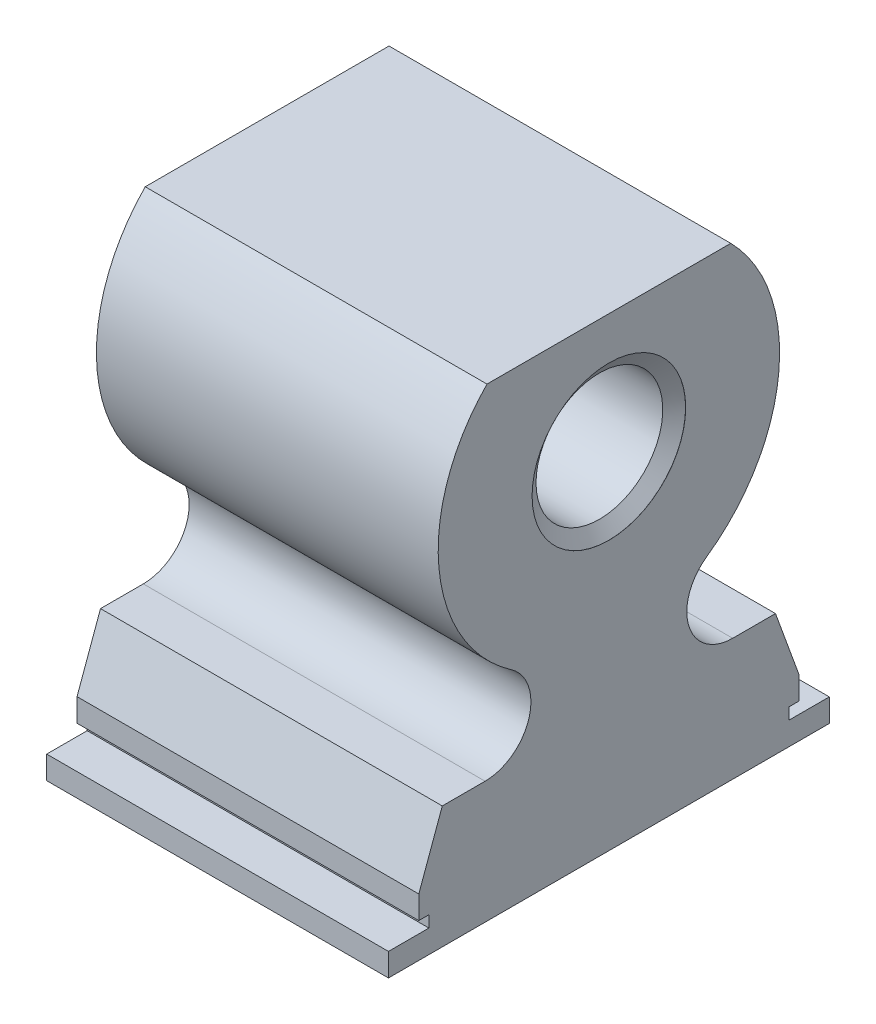
SolidWorks part; units mm, degrees
extrude "Body" add sketch "BodySke" along normal blind 8.9
sketch "BodySke" plane through (0, 0, 0) normal (1, 0, 0) x (0, 0, -1)
  line L0 (-5.74, -9) -> (5.74, -9)
  line L1 (5.74, -9) -> (5.74, -8.4)
  line L2 (5.74, -8.4) -> (4.6867, -8.4)
  line L3 (-5.74, -9) -> (-5.74, -8.4)
  line L4 (-5.74, -8.4) -> (-4.6867, -8.4)
  line L5 (4.6867, -8.4) -> (4.6867, -8.1)
  line L6 (-4.6867, -8.4) -> (-4.6867, -8.1)
  line L7 (4.6867, -8.1) -> (4.95, -8.1)
  line L8 (-4.6867, -8.1) -> (-4.95, -8.1)
  line L9 (-3.2237, -5.82) -> (-4.3385, -5.82)
  line L10 (0, -0.7) -> (4.5045, -0.7) construction
  line L11 (4.3385, -5.82) -> (3.2237, -5.82)
  line L12 (0, 7.62) -> (0, -11.43) construction
  line L13 (7.62, 0) -> (-7.62, 0) construction
  line L14 (2.03, -2.8908) -> (2.03, -7.62) construction
  line L15 (-2.03, -2.8908) -> (-2.03, -7.62) construction
  line L16 (4.3385, -5.82) -> (4.95, -7.5)
  line L17 (4.95, -7.5) -> (4.95, -8.1)
  line L18 (-4.3385, -5.82) -> (-4.95, -7.5)
  line L19 (-4.95, -7.5) -> (-4.95, -8.1)
  circle A0 centre (0, 0) radius 1.65
  arc A1 (2.5412, -3.6469) -> (-2.5412, -3.6469) centre (0, 0) ccw
  arc A2 (3.2237, -5.82) -> (2.5412, -3.6469) centre (3.2237, -4.6263) cw
  arc A3 (-2.5412, -3.6469) -> (-3.2237, -5.82) centre (-3.2237, -4.6263) cw
  dimension "Thread_min" = 3.3
  dimension "C_dia" = 8.89
  dimension "J_dim" = 4.06
  dimension "E_dim" = 11.48
  dimension "D_dim" = 3.18
  dimension "Clinch_ht" = 0.6
  dimension "Side_ht" = 0.6
  dimension "Groove_wid" = 0.3
  dimension "A_dim" = 9.9
  dimension "Groove_overall" = 9.3733
  dimension "F_dim" = 9
  dimension "D12" = 20
  dimension "Advance" = 0.7
cosmetic thread "ThreadCosmetic" [suppressed]
revolve "EndChamfer" cut sketch "EndChamferSke" angle 360 about L11
sketch "EndChamferSke" plane through (0, 0, 0) normal (0, 0, 1) x (1, 0, 0)
  line L0 (-0.254, 2) -> (0.0025, 2)
  line L2 (0.0025, 2) -> (0.2475, 1.65)
  line L3 (0.2475, 1.65) -> (-0.254, 1.65)
  line L4 (-0.254, 1.65) -> (-0.254, 2)
  line L5 (9.154, 2) -> (8.8975, 2)
  line L6 (8.8975, 2) -> (8.6525, 1.65)
  line L7 (8.6525, 1.65) -> (9.154, 1.65)
  line L8 (9.154, 1.65) -> (9.154, 2)
  line L9 (0, 4.445) -> (0, -3.6469) construction
  line L10 (8.9, -3.6469) -> (8.9, 4.445) construction
  line L11 (-5.1059, 0) -> (14.0173, 0) construction
  line L12 (8.9, 0) -> (0, 0) construction
  dimension "Thread_min" = 3.3
  dimension "D3" = 0.254
  dimension "D4" = 0.254
  dimension "Thread_nominal" = 4
  dimension "D2" = 34.99
ref_plane "Plane1" through (0, 0, 0) normal (0, 0, 1) x (1, 0, 0)
ref_plane "Plane2" through (0, 0, 0) normal (0, 1, 0) x (1, 0, 0)
ref_plane "Plane3" through (0, 0, 0) normal (1, 0, 0) x (0, 0, -1)
sketch "ThdSchSke" [suppressed] plane through (0, 0, 0) normal (0, 0, 1) x (1, 0, 0)
  line L0 (-1.2331, 0) -> (11.43, 0) construction
  line L1 (6.0414, 0) -> (0.207, 0) construction
  line L2 (0.0025, 1.7272) -> (0.0025, -1.4224) construction
  line L3 (0.0025, -1.4224) -> (0.2071, -1.1303)
  line L4 (0.207, -1.1303) -> (6.0414, -1.1303) construction
  line L5 (0.0025, -1.4224) -> (-0.202, -1.1303)
  line L6 (-0.202, -1.1303) -> (0.2071, -1.1303)
  line L8 (0.0025, 1.4224) -> (0.0025, -1.4224) construction
  dimension "Thread_nominal" = 4
revolve "ThreadSchematic" [suppressed] cut sketch "ThdSchSke" angle 360 about L0
pattern_linear "ThdSchPat" [suppressed]
sketch "TopCutSke" plane through (0, 0, 0) normal (-1, 0, 0) x (0, 0, 1)
  line L0 (0, 0) -> (0, 6.35) construction
  line L1 (-4.445, 3.1115) -> (4.445, 3.1115)
  line L2 (-4.445, 3.1115) -> (-4.445, 12.0015)
  line L3 (-4.445, 12.0015) -> (4.445, 12.0015)
  line L4 (4.445, 3.1115) -> (4.445, 12.0015)
  dimension "Width" = 8.89
  dimension "Offset" = 3.1115
extrude "TopCut" cut sketch "TopCutSke" against normal blind 8.9
equation "' \"Length@Body\" = 8.9"
equation "' \"A_dim@BodySke\" = 9.9"
equation "' \"C_dia@BodySke\" = 8.89"
equation "' \"D_dim@BodySke\" = 3.18"
equation "' \"E_dim@BodySke\" = 11.48"
equation "' \"F_dim@BodySke\" = 9"
equation "' \"J_dim@BodySke\" =  4.06"
equation "' \"J_dim@BodySke\" = 4.06"
equation "' \"Advance@BodySke\" = 0.7"
equation "' \"Thread_min@BodySke\" = 3.3"
equation "' \"Thread_nominal@ThreadCosmetic\" = 4"
equation "\"Width@TopCutSke\" = \"C_dia@BodySke\""
equation "\"Offset@TopCutSke\" = \"C_dia@BodySke\" * 0.35"
equation "\"Length@TopCut\" = \"Length@Body\""
equation "\"Clinch_ht@BodySke\" = 1 * 0.6"
equation "\"Groove_wid@BodySke\" = \"Clinch_ht@BodySke\" / 2"
equation "\"Groove_overall@BodySke\" = \"A_dim@BodySke\" - ( \"E_dim@BodySke\" - \"A_dim@BodySke\") / 3"
equation "\"Side_ht@BodySke\" = \"Clinch_ht@BodySke\""
equation "\"Thread_nominal@EndChamferSke\" = \"Thread_nominal@ThreadCosmetic\""
equation "\"Thread_min@EndChamferSke\" = \"Thread_min@BodySke\""
equation "\"D2@EndChamferSke\" = \"Vee_angle@ThdSchSke\" / 2 - 0.01"
equation "\"Thread_nominal@ThdSchSke\" = \"Thread_nominal@ThreadCosmetic\""
equation "\"Num_threads@ThdSchPat\" = int(  ( \"Length@Body\" - \"Inset@EndChamferSke\" - \"Inset_far@EndChamferSke\" ) / \"Advance@BodySke\" + 0.999 )  + 1"
equation "\"Advance@ThdSchPat\" = (  \"Length@Body\" - \"Inset@EndChamferSke\" - \"Inset_far@EndChamferSke\"  ) /  (\"Num_threads@ThdSchPat\" - 1) 'relax it"
